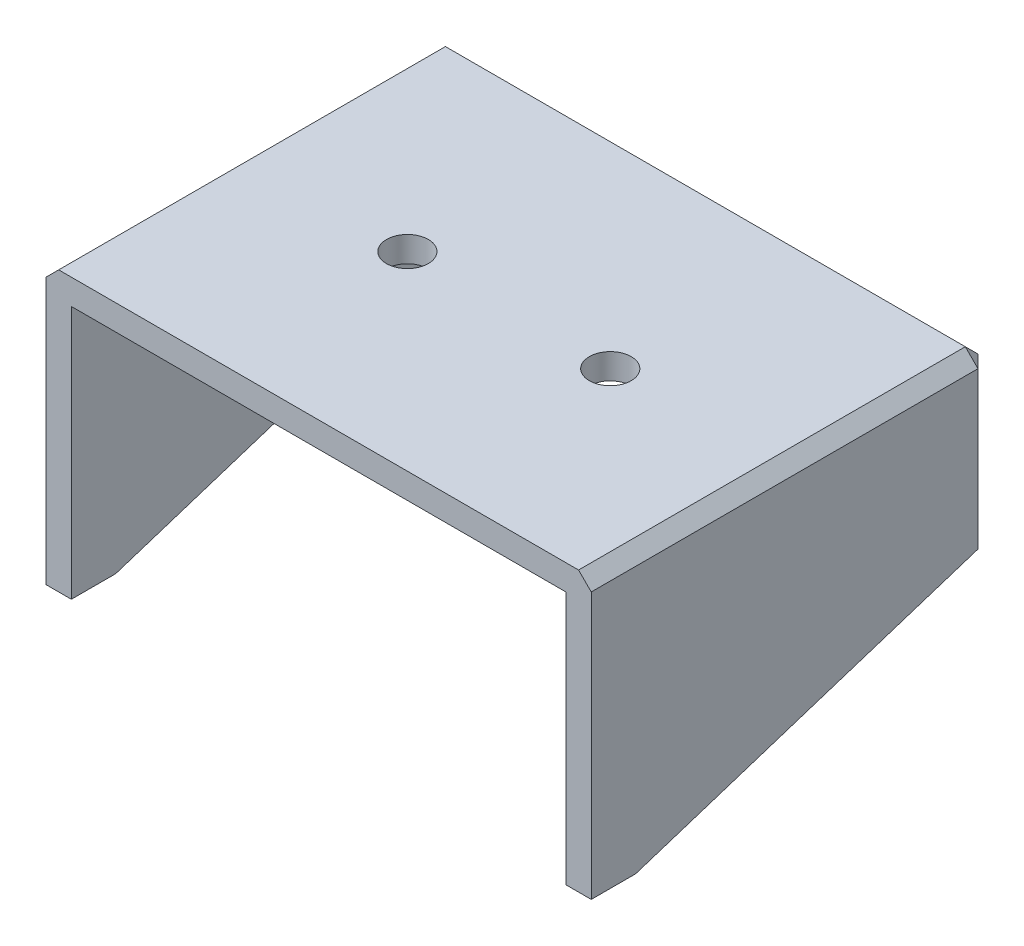
SolidWorks part; units mm, degrees
ref_plane "前视基准面" through (0, 0, 0) normal (0, 0, 1) x (1, 0, 0)
ref_plane "上视基准面" through (0, 0, 0) normal (0, 1, 0) x (1, 0, 0)
ref_plane "右视基准面" through (0, 0, 0) normal (1, 0, 0) x (0, 0, -1)
sketch "草图1" plane through (0, 0, 0) normal (0, 1, 0) x (1, 0, 0)
  line L0 (0, 0) -> (0, 18.1294) construction
  line L1 (-21.5, 10.4831) -> (21.5, 10.4831)
  line L2 (-21.5, 10.4831) -> (-21.5, -21.0169)
  line L3 (-21.5, -21.0169) -> (21.5, -21.0169)
  line L4 (21.5, 10.4831) -> (21.5, -21.0169)
  line L5 (0, 18.1294) -> (0, -22.8026) construction
  dimension "D1" = 21.5
  dimension "49" = 43
  dimension "D2" = 31.5
extrude "凸台-拉伸1" add sketch "草图1" along normal blind 2
sketch "草图4" plane through (0, 0, 0) normal (0, -1, 0) x (1, 0, 0)
  line L0 (-21.5, 21.0169) -> (21.5, 21.0169) construction
  line L1 (-21.5, 21.0169) -> (-19.5, 21.0169)
  line L2 (-21.5, 21.0169) -> (-21.5, -10.4831)
  line L3 (-21.5, -10.4831) -> (-19.5, -10.4831)
  line L4 (-19.5, 21.0169) -> (-19.5, -10.4831)
  line L5 (-21.5, -10.4831) -> (-21.5, 21.0169) construction
  line L6 (21.5, -10.4831) -> (-21.5, -10.4831) construction
  line L8 (21.5, 21.0169) -> (19.5, 21.0169)
  line L9 (21.5, 21.0169) -> (21.5, -10.4831)
  line L10 (21.5, -10.4831) -> (19.5, -10.4831)
  line L11 (19.5, 21.0169) -> (19.5, -10.4831)
  dimension "D1" = 2
  dimension "D2" = 2
extrude "凸台-拉伸3" add sketch "草图4" along normal blind 20 contours L9 L8 L11 L10 | L2 L1 L4 L3
sketch "草图7" plane through (0, 0, 0) normal (0, -1, 0) x (1, 0, 0)
  line L1 (19.5, -10.4831) -> (-19.5, -10.4831)
  line L2 (19.5, -10.4831) -> (19.5, -8.9831)
  line L3 (19.5, -8.9831) -> (-19.5, -8.9831)
  line L4 (-19.5, -10.4831) -> (-19.5, -8.9831)
  line L5 (-19.5, 21.0169) -> (-19.5, -10.4831) construction
  dimension "D1" = 1.5
extrude "凸台-拉伸4" add sketch "草图7" along normal blind 11
sketch "草图6" plane through (0, 0, 0) normal (0, -1, 0) x (1, 0, 0)
  line L0 (21.5, 21.0169) -> (21.5, -10.4831) construction
  line L1 (-19.5, 21.0169) -> (19.5, 21.0169) construction
  circle A0 centre (8, 6.0169) radius 1.65
  circle A1 centre (-8, 6.0169) radius 1.65
  dimension "D5" = 3.3
  dimension "D6" = 3.3
  dimension "D1" = 16
  dimension "D2" = 13.5
  dimension "D3" = 15
  dimension "D4" = 15
extrude "切除-拉伸2" cut sketch "草图6" against normal blind 12
sketch "草图5" plane through (0, 0, -10.4831) normal (0, 0, -1) x (-1, 0, 0)
  line L1 (-21.5, 2) -> (-21.5, -20) construction
  line L2 (19.5, -11) -> (-19.5, -11) construction
  line L4 (21.5, 2) -> (21.5, -20) construction
  circle A0 centre (-13, -3) radius 1.5
  circle A1 centre (13, -3) radius 1.5
  dimension "D1" = 8.5
  dimension "D2" = 8
  dimension "D7" = 8.5
  dimension "D8" = 3
  dimension "D9" = 3
  dimension "D3" = 8
extrude "切除-拉伸1" cut sketch "草图5" against normal blind 12
chamfer "倒角1" distance 1 angle 45 5 edges at (-21.5, -9, -10.4831) (-21.5, 2, 5.2669) (21.5, -9, -10.4831) (0, 2, -10.4831) (21.5, 2, 5.2669)
sketch "草图10" plane through (-19.5, 0, 0) normal (1, 0, 0) x (0, 0, -1)
  line L1 (10.4831, -20) -> (10.4831, -11)
  line L3 (10.4831, 1) -> (10.4831, -20) construction
  line L5 (10.4831, -11) -> (-17.5169, -20)
  line L12 (10.4831, -20) -> (-17.5169, -20)
  line L13 (-21.0169, -20) -> (9.4831, -20) construction
  dimension "D1" = 9
extrude "切除-拉伸4" cut sketch "草图10" against normal mid plane 100
sketch "草图13" plane through (0, 0, -10.4831) normal (0, 0, -1) x (-1, 0, 0)
  line L1 (-19.5, -11) -> (19.5, -11)
  line L2 (-19.5, -11) -> (-19.5, -7)
  line L3 (-19.5, -7) -> (19.5, -7)
  line L4 (19.5, -11) -> (19.5, -7)
  dimension "D1" = 4
extrude "切除-拉伸8" cut sketch "草图13" against normal blind 10
sketch "草图14" plane through (0, 0, -10.4831) normal (0, 0, -1) x (-1, 0, 0)
  line L0 (0, 0) -> (0, -3.3771) construction
  line L1 (-21.5, -11.3214) -> (-21.5, 1) construction
  line L2 (-20.5, 2) -> (20.5, 2) construction
  circle A0 centre (-13, -4) radius 1.5
  circle A1 centre (13, -4) radius 1.5
  dimension "D1" = 3
  dimension "D2" = 8.5
  dimension "D3" = 6
extrude "切除-拉伸9" [suppressed] cut sketch "草图14" against normal blind 10
sketch "草图15" plane through (21.5, 0, 0) normal (1, 0, 0) x (0, 0, -1)
  line L0 (-21.0169, -20) -> (-26.56, -20)
  line L1 (-26.56, -20) -> (-21.0169, -10)
  line L2 (-21.0169, 1) -> (-21.0169, -20) construction
  line L3 (-21.0169, -20) -> (-21.0169, -10)
  dimension "D1" = 29
  dimension "D2" = 10
extrude "凸台-拉伸5" [suppressed] add sketch "草图15" against normal blind 2
mirror "镜向1" [suppressed] about plane through (0, 0, 0) normal (1, 0, 0)
